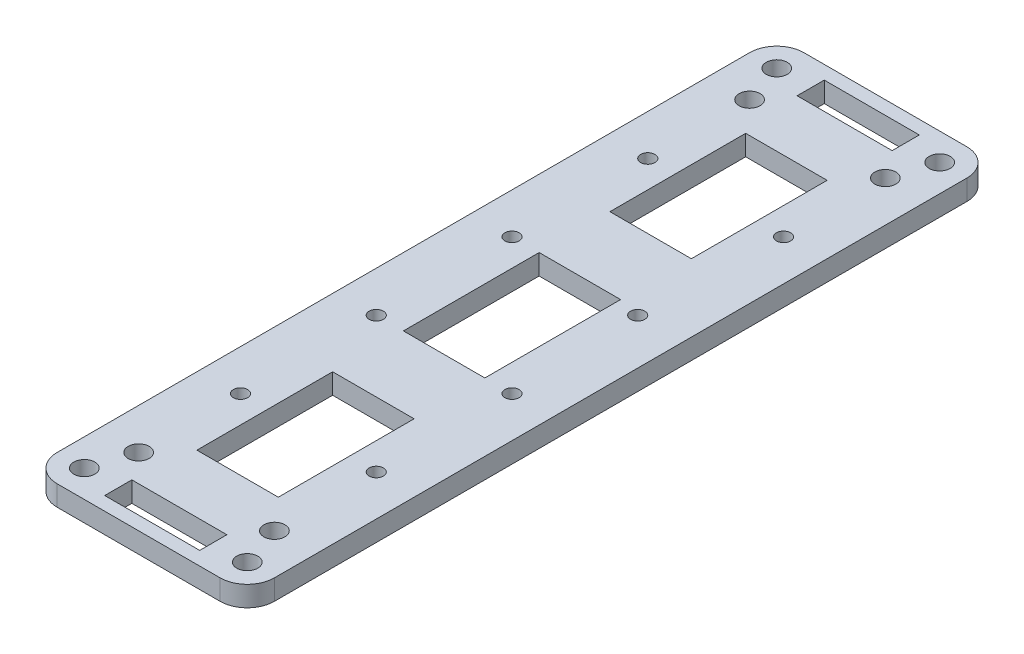
SolidWorks part; units mm, degrees
ref_plane "前视基准面" through (0, 0, 0) normal (0, 0, 1) x (1, 0, 0)
ref_plane "上视基准面" through (0, 0, 0) normal (0, 1, 0) x (1, 0, 0)
ref_plane "右视基准面" through (0, 0, 0) normal (1, 0, 0) x (0, 0, -1)
other "Configuration Table"
sketch "草图1" plane through (0, 0, 0) normal (0, 1, 0) x (1, 0, 0)
  line L0 (-6, 20.4225) -> (6, 20.4225)
  line L2 (6, 40.4225) -> (6, 20.4225)
  line L7 (-16, 7.5056) -> (-16, -7.5056)
  line L8 (-6, 40.4225) -> (6, 40.4225)
  line L10 (-6, 40.4225) -> (-6, 20.4225)
  line L19 (-16, -37.4761) -> (-16, -51)
  line L23 (-12, -55) -> (12, -55)
  line L54 (16, 0) -> (-16, 0) construction
  line L55 (0, 55) -> (0, 49) construction
  line L78 (16, -37.4761) -> (16, -51)
  line L100 (-16, 31.1424) -> (-16, 51)
  line L116 (16, 25.4671) -> (16, 51)
  line L117 (-16, -51) -> (-16, -37.4761)
  line L118 (16, -51) -> (16, -37.4761)
  line L136 (0, 10) -> (0, -55) construction
  line L137 (9.6638, 43.4869) -> (10, 45) construction
  line L143 (-12, 55) -> (12, 55)
  line L151 (-10, 10) -> (10, -10) construction
  line L152 (0, -10) -> (0, 10) construction
  line L157 (-10, 10) -> (10, -10) construction
  line L158 (-10, -10) -> (9.2575, 9.2575) construction
  line L169 (-10, 30) -> (10, -30) construction
  line L170 (-10, -30) -> (10, 30) construction
  line L176 (-7, 53) -> (7, 53)
  line L181 (0, 0) -> (10, -45) construction
  line L182 (-10, -45) -> (0, 0) construction
  line L183 (-6, -40.4225) -> (6, -40.4225)
  line L184 (-6, -40.4225) -> (-6, -20.4225)
  line L185 (-6, -20.4225) -> (6, -20.4225)
  line L186 (6, -40.4225) -> (6, -20.4225)
  line L187 (-6, -40.4225) -> (6, -20.4225) construction
  line L188 (-6, -20.4225) -> (6, -40.4225) construction
  line L189 (-7, -49) -> (7, -49)
  line L190 (-7, -49) -> (-7, -53)
  line L191 (-7, -53) -> (7, -53)
  line L192 (7, -49) -> (7, -53)
  line L193 (-7, -49) -> (7, -53) construction
  line L194 (-7, -53) -> (7, -49) construction
  line L195 (7, 49) -> (7, 53)
  line L196 (-7, 49) -> (7, 49)
  line L197 (-7, 49) -> (-7, 53)
  line L202 (-16, -37.4761) -> (-16, 31.1424)
  line L207 (-10, 10) -> (10, -10) construction
  line L208 (-10, -10) -> (9.2575, 9.2575) construction
  line L209 (-6, 10) -> (6, 10)
  line L210 (-6, 10) -> (-6, -10)
  line L211 (-6, -10) -> (6, -10)
  line L212 (6, 10) -> (6, -10)
  line L215 (16, -37.4761) -> (16, 25.4671)
  arc A5 (-16, -51) -> (-12, -55) centre (-12, -51) ccw
  arc A6 (16, -51) -> (12, -55) centre (12, -51) cw
  arc A17 (16, 51) -> (12, 55) centre (12, 51) ccw
  arc A18 (-16, 51) -> (-12, 55) centre (-12, 51) cw
  circle A24 centre (-10, 30) radius 1.05
  circle A25 centre (10, 30) radius 1.05
  circle A26 centre (-10, 10) radius 1.05
  circle A29 centre (10, -10) radius 1.05
  circle A30 centre (-10, -30) radius 1.05
  circle A31 centre (10, -30) radius 1.05
  circle A41 centre (10, -45) radius 1.55
  circle A42 centre (-10, -45) radius 1.55
  circle A43 centre (10, 45) radius 1.55
  circle A44 centre (-10, 45) radius 1.55
  circle A45 centre (9.2575, 9.2575) radius 1.05
  circle A46 centre (-10, -10) radius 1.05
  circle A52 centre (-12, 51) radius 1.55
  circle A53 centre (12, 51) radius 1.55
  circle A54 centre (-12, -51) radius 1.55
  circle A55 centre (12, -51) radius 1.55
  point P2 (0, 0)
  point P112 (0, 0)
  point P194 (0, 0)
  point P203 (-0.3712, -0.3712)
  point P208 (0, 0)
  point P229 (0, 0)
  point P239 (0, -30.4225)
  point P244 (0, -51)
  dimension "D2" = 4
  dimension "D3" = 12
  dimension "D4" = 20
  dimension "D11" = 24
  dimension "D8" = 20
  dimension "D9" = 90
  dimension "D5" = 14
  dimension "D6" = 4
extrude "凸台-拉伸1" add sketch "草图1" along normal blind 3 contours A42 | A41 | A31 | A30 | L183 L186 L185 L184 | A46 | A29 | A45 | A26 | L8 | A25 | A24 | A44 | L197 L196 L195 L176 | A43 | L192 L189 L190 L191
